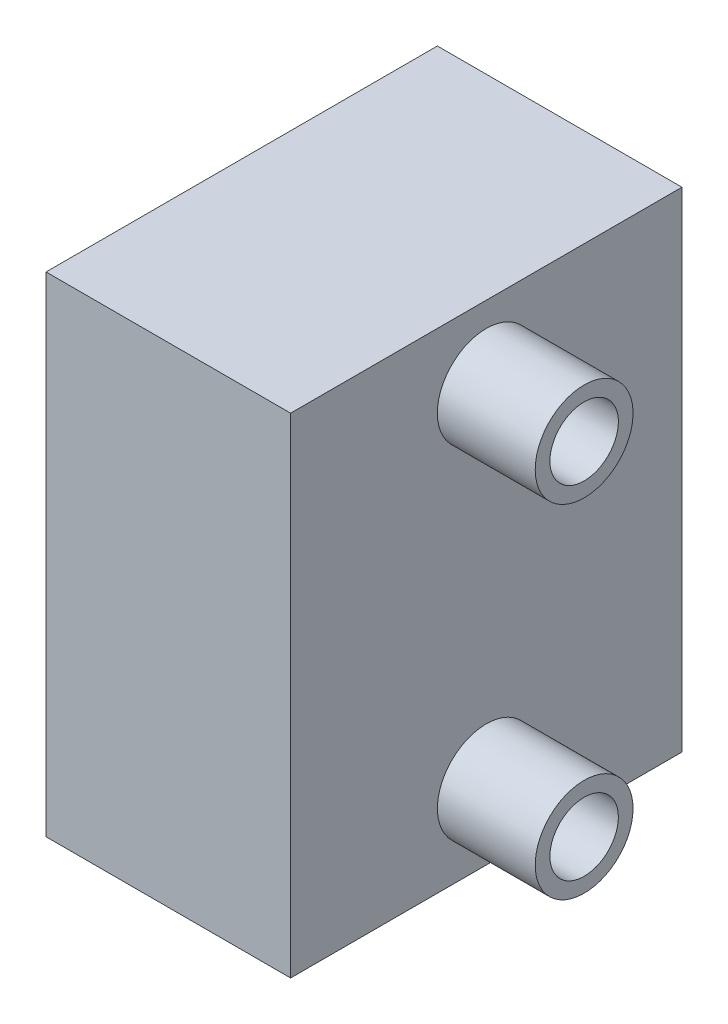
SolidWorks part; units mm, degrees
ref_plane "Front Plane" through (0, 0, 0) normal (1, 0, 0) x (0, 1, 0)
ref_plane "Top Plane" through (0, 0, 0) normal (0, 0, 1) x (0, 1, 0)
ref_plane "Right Plane" through (0, 0, 0) normal (0, 1, 0) x (-1, 0, 0)
sketch "Sketch1" plane through (0, 0, 0) normal (1, 0, 0) x (0, 1, 0)
  line L1 (50, -40) -> (-50, -40)
  line L2 (50, -40) -> (50, 40)
  line L3 (50, 40) -> (-50, 40)
  line L4 (-50, -40) -> (-50, 40)
  line L5 (50, -40) -> (-50, 40) construction
  line L6 (50, 40) -> (-50, -40) construction
  point P0 (0, 0)
  dimension "D1" = 80
  dimension "D2" = 100
extrude "Boss-Extrude1" add sketch "Sketch1" along normal blind 50
sketch "Sketch2" plane through (50, 0, 0) normal (1, 0, 0) x (0, 1, 0)
  line L0 (0, 0) -> (0, 40) construction
  line L1 (50, 40) -> (-50, 40) construction
  circle A0 centre (-35, 0) radius 10
  circle A2 centre (-35, 0) radius 7
  circle A3 centre (35, 0) radius 7
  circle A4 centre (35, 0) radius 10
  dimension "D2" = 20
  dimension "D3" = 14
  dimension "D1" = 35
extrude "Boss-Extrude2" add sketch "Sketch2" along normal blind 20
